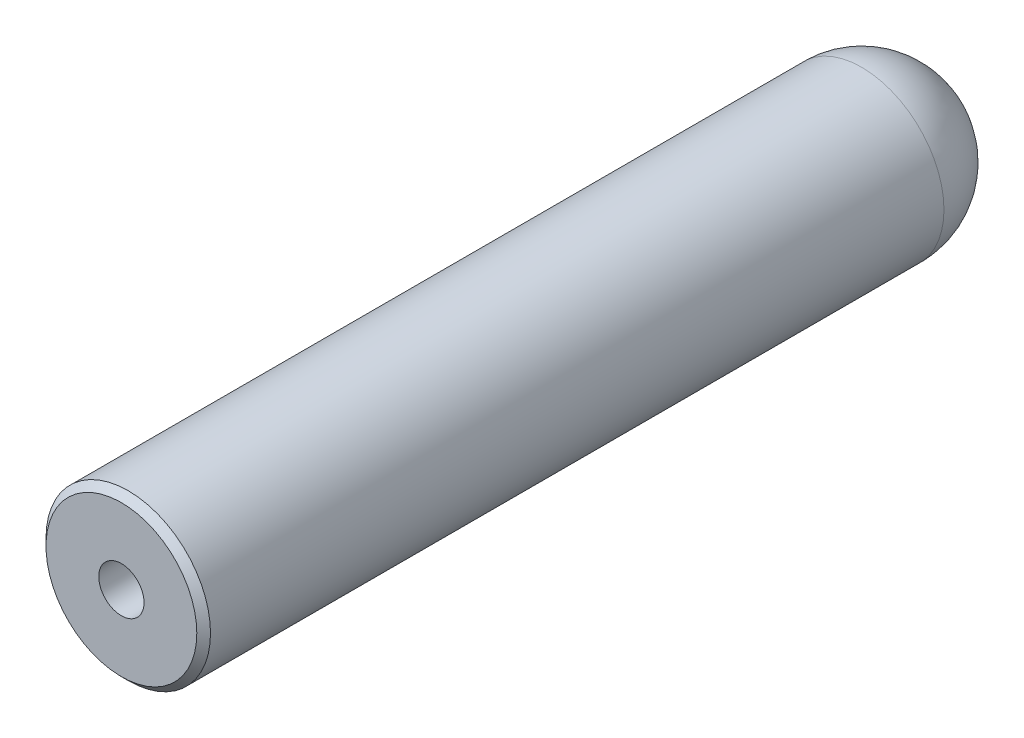
SolidWorks part; units mm, degrees
ref_plane "前基準面" through (0, 0, 0) normal (0, 0, 1) x (1, 0, 0)
ref_plane "上基準面" through (0, 0, 0) normal (0, 1, 0) x (1, 0, 0)
ref_plane "右基準面" through (0, 0, 0) normal (1, 0, 0) x (0, 0, -1)
sketch "草圖1" plane through (0, 0, 0) normal (0, 0, 1) x (1, 0, 0)
  circle A0 centre (0, 0) radius 6
  dimension "D1" = 12
extrude "伸長1" add sketch "草圖1" along normal blind 60
fillet "圓角1" radius 6 1 edges at (6, 0, 0)
chamfer "導角1" distance 0.5 angle 45 1 edges at (6, 0, 60)
hole_wizard "M4 螺紋孔1" positions "3D草圖1" profile "草圖2" tap size "M4" standard "ISO"
sketch3d "3D草圖1"
  circle A0 centre (0, 0, 59.5) radius 6 construction
  circle A1 centre (0, 0, 6) radius 6 construction
  point P0 (0, 0, 60)
  point P5 (0, 0, 53.5)
  point P8 (0, 0, 12)
sketch "草圖2" plane through (0, 0, 60) normal (1, 0, 0) x (0, -1, 0)
  line L0 (0, 0) -> (0, 12.4914)
  line L1 (0, 12.4914) -> (1.65, 11.5)
  line L2 (1.65, 11.5) -> (1.65, 0)
  line L5 (1.65, 0) -> (0, 0)
  line L10 (0, 12.4914) -> (-1.65, 11.5) construction
  line L11 (0, -6.35) -> (0, 107.95) construction
  dimension "螺孔鑽直徑" = 3.3
  dimension "螺孔鑽深度" = 11.5
  dimension "導頭角度" = 118
cosmetic thread "鑽孔螺紋1" parameters "D1"=8, "D2"=4
